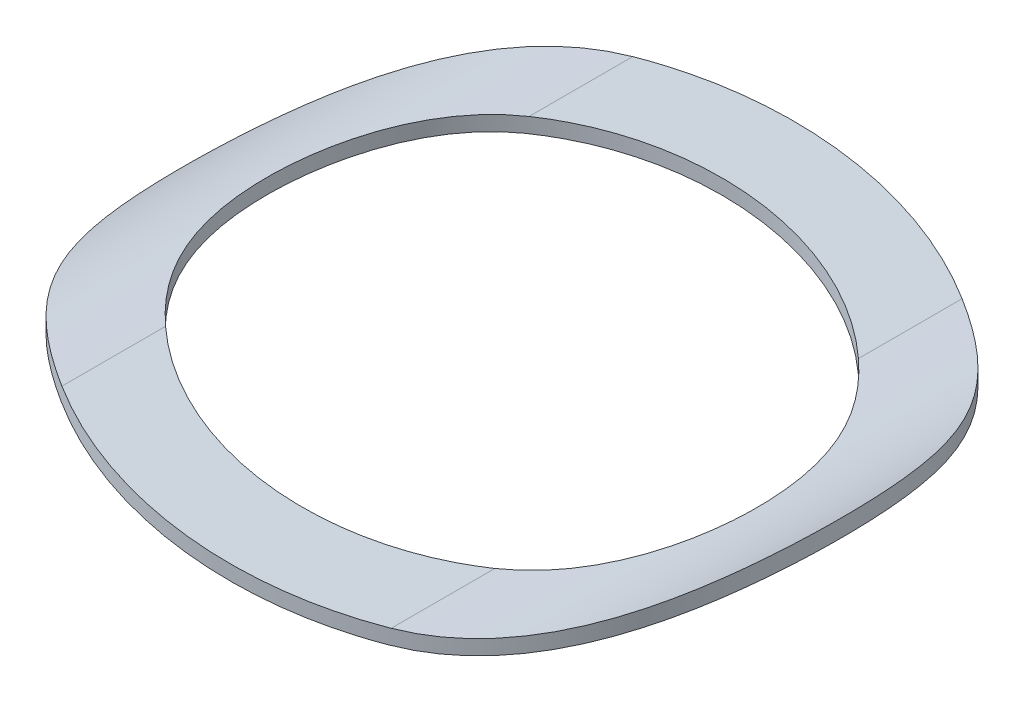
SolidWorks part; units mm, degrees
ref_plane "Front Plane" through (0, 0, 0) normal (0, 0, 1) x (1, 0, 0)
ref_plane "Top Plane" through (0, 0, 0) normal (0, 1, 0) x (1, 0, 0)
ref_plane "Right Plane" through (0, 0, 0) normal (1, 0, 0) x (0, 0, -1)
sketch "Sketch1" plane through (0, 0, 0) normal (0, 0, 1) x (1, 0, 0)
  line L0 (0, 0) -> (54.6131, 0) construction
  line L1 (-21.1111, -2) -> (56.808, -2) construction
  line L2 (6.6465, -1.908) -> (-6.6465, -0.092)
  arc A0 (-6.6465, -0.092) -> (-14, -2) centre (-8, -10) ccw
  arc A1 (6.6465, -1.908) -> (14, 0) centre (8, 8) ccw
  dimension "D4" = 20
  dimension "D1" = 2
  dimension "D2" = 8
  dimension "D3" = 8
extrude "Extrude-Thin1" add sketch "Sketch1" along normal mid plane 30 thin thin type one direction wall 0.6
sketch "Sketch2" plane through (0, 0, 0) normal (0, 1, 0) x (1, 0, 0)
  circle A0 centre (0, 0) radius 13.3
  circle A1 centre (0, 0) radius 9.9
  dimension "D1" = 26.6
  dimension "D2" = 19.8
extrude "Extrude1" cut sketch "Sketch2" against normal blind 30 flip side to cut
equation "\"D3@Sketch1\" = \"D2@Sketch1\""
